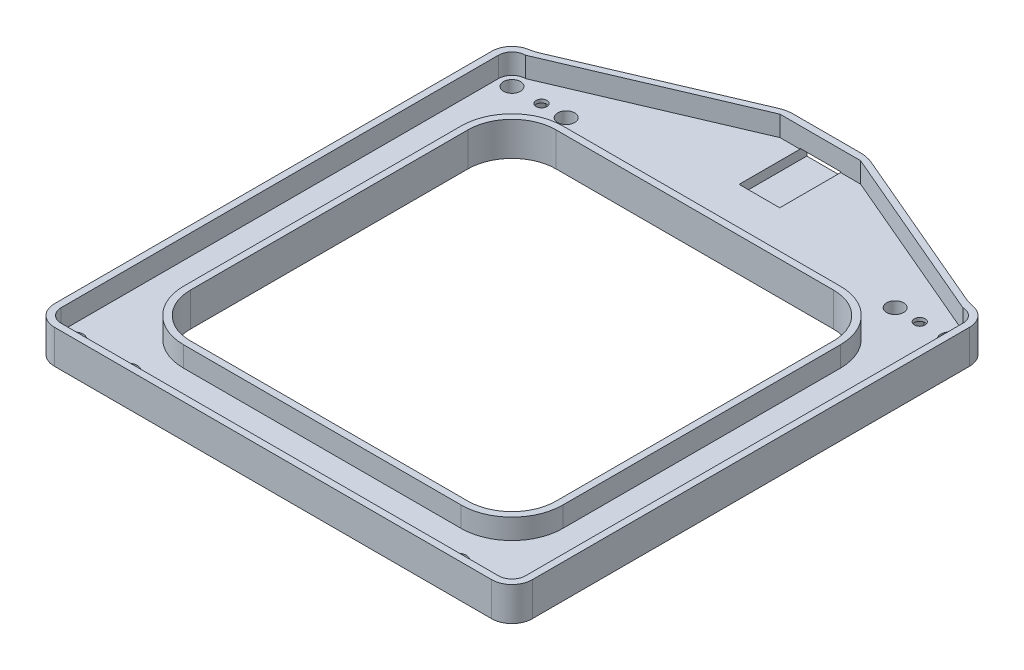
SolidWorks part; units mm, degrees
ref_plane "Front Plane" through (0, 0, 0) normal (0, 0, 1) x (1, 0, 0)
ref_plane "Top Plane" through (0, 0, 0) normal (0, 1, 0) x (1, 0, 0)
ref_plane "Right Plane" through (0, 0, 0) normal (1, 0, 0) x (0, 0, -1)
sketch "Sketch1" plane through (0, 0, 0) normal (0, 1, 0) x (1, 0, 0)
  line L0 (-64.6, 70.6) -> (-13.7811, 92.2969)
  line L5 (-64.6, -70.6) -> (64.6, -70.6)
  line L6 (-70.6, -64.6) -> (-70.6, 64.6)
  line L7 (-64.6, 70.6) -> (64.6, 70.6) construction
  line L8 (70.6, -64.6) -> (70.6, 64.6)
  line L9 (-70.6, -70.6) -> (70.6, 70.6) construction
  line L10 (-70.6, 70.6) -> (70.6, -70.6) construction
  line L11 (-41, -54) -> (41, -54)
  line L12 (-54, -41) -> (-54, 41)
  line L13 (-41, 54) -> (41, 54)
  line L14 (54, -41) -> (54, 41)
  line L15 (-54, -54) -> (54, 54) construction
  line L16 (-54, 54) -> (54, -54) construction
  line L17 (-9.8546, 93.1) -> (9.8546, 93.1)
  line L18 (13.7811, 92.2969) -> (64.6, 70.6)
  arc A0 (-70.6, -64.6) -> (-64.6, -70.6) centre (-64.6, -64.6) ccw
  arc A1 (64.6, -70.6) -> (70.6, -64.6) centre (64.6, -64.6) ccw
  arc A2 (70.6, 64.6) -> (64.6, 70.6) centre (64.6, 64.6) ccw
  arc A3 (-64.6, 70.6) -> (-70.6, 64.6) centre (-64.6, 64.6) ccw
  arc A4 (-54, -41) -> (-41, -54) centre (-41, -41) ccw
  arc A5 (41, -54) -> (54, -41) centre (41, -41) ccw
  arc A6 (54, 41) -> (41, 54) centre (41, 41) ccw
  arc A7 (-41, 54) -> (-54, 41) centre (-41, 41) ccw
  arc A8 (13.7811, 92.2969) -> (9.8546, 93.1) centre (9.8546, 83.1) ccw
  arc A9 (-9.8546, 93.1) -> (-13.7811, 92.2969) centre (-9.8546, 83.1) ccw
  point P0 (0, 0)
  point P18 (0, 0)
  point P39 (11.9, 93.1)
  point P42 (-11.9, 93.1)
  dimension "D3" = 6
  dimension "D6" = 13
  dimension "D9" = 10
  dimension "D1" = 141.2
  dimension "D2" = 141.2
  dimension "D4" = 108
  dimension "D5" = 108
  dimension "D7" = 22.5
  dimension "D8" = 23.8
extrude "Boss-Extrude1" add sketch "Sketch1" along normal blind 10
sketch "Sketch2" plane through (0, 10, 0) normal (0, 1, 0) x (1, 0, 0)
  line L0 (-64.6, 68.6) -> (-11.9, 91.1)
  line L1 (-64.6, -68.6) -> (64.6, -68.6)
  line L2 (-68.6, -64.6) -> (-68.6, 64.6)
  line L3 (-64.6, 68.6) -> (64.6, 68.6) construction
  line L4 (68.6, -64.6) -> (68.6, 64.6)
  line L5 (-68.6, -68.6) -> (68.6, 68.6) construction
  line L6 (-68.6, 68.6) -> (68.6, -68.6) construction
  line L7 (-41, -56) -> (41, -56)
  line L8 (-56, -41) -> (-56, 41)
  line L9 (-41, 56) -> (41, 56)
  line L10 (56, -41) -> (56, 41)
  line L11 (-56, -56) -> (56, 56) construction
  line L12 (-56, 56) -> (56, -56) construction
  line L13 (-11.9, 91.1) -> (11.9, 91.1)
  line L14 (11.9, 91.1) -> (64.6, 68.6)
  line L16 (-13.7811, 92.2969) -> (-64.6, 70.6) construction
  arc A0 (-68.6, -64.6) -> (-64.6, -68.6) centre (-64.6, -64.6) ccw
  arc A1 (64.6, -68.6) -> (68.6, -64.6) centre (64.6, -64.6) ccw
  arc A2 (68.6, 64.6) -> (64.6, 68.6) centre (64.6, 64.6) ccw
  arc A3 (-64.6, 68.6) -> (-68.6, 64.6) centre (-64.6, 64.6) ccw
  arc A4 (-56, -41) -> (-41, -56) centre (-41, -41) ccw
  arc A5 (41, -56) -> (56, -41) centre (41, -41) ccw
  arc A6 (56, 41) -> (41, 56) centre (41, 41) ccw
  arc A7 (-41, 56) -> (-56, 41) centre (-41, 41) ccw
  point P0 (0, 0)
  point P8 (0, 91.1)
  point P20 (0, 0)
  point P44 (0, 68.6)
  dimension "D3" = 4
  dimension "D6" = 15
  dimension "D1" = 2
  dimension "D2" = 2
  dimension "D4" = 2
  dimension "D5" = 2
  dimension "D7" = 2
extrude "Cut-Extrude1" cut sketch "Sketch2" against normal blind 6
sketch "Sketch3" plane through (0, 0, 0) normal (0, 1, 0) x (1, 0, 0)
  line L4 (0, -5.5) -> (0, 5.5) construction
  line L6 (-5.5, 0) -> (5.5, 0) construction
  circle A0 centre (-64.6, 64.6) radius 2.5
  circle A1 centre (-48.6, 64.6) radius 2.5
  circle A14 centre (-55.87, 64.6) radius 1.6
  circle A15 centre (55.87, 64.6) radius 1.6
  circle A16 centre (48.6, 64.6) radius 2.5
  circle A17 centre (64.6, 64.6) radius 2.5
  circle A18 centre (64.6, -64.6) radius 2.5
  circle A19 centre (48.6, -64.6) radius 2.5
  circle A20 centre (55.87, -64.6) radius 1.6
  circle A21 centre (-55.87, -64.6) radius 1.6
  circle A22 centre (-48.6, -64.6) radius 2.5
  circle A23 centre (-64.6, -64.6) radius 2.5
  dimension "D1" = 5
  dimension "D6" = 3.2
  dimension "D2" = 6
  dimension "D3" = 6
  dimension "D4" = 16
  dimension "D5" = 7.27
extrude "Cut-Extrude5" cut sketch "Sketch3" along normal through all
sketch "Sketch6" plane through (0, 0, 0) normal (0, -1, 0) x (1, 0, 0)
  line L0 (5.5, 0) -> (-5.5, 0) construction
  line L1 (-52.4059, 64.6) -> (-54.1379, 67.6)
  line L2 (-54.1379, 67.6) -> (-57.6021, 67.6)
  line L3 (-57.6021, 67.6) -> (-59.3341, 64.6)
  line L4 (-59.3341, 64.6) -> (-57.6021, 61.6)
  line L5 (-57.6021, 61.6) -> (-54.1379, 61.6)
  line L6 (-54.1379, 61.6) -> (-52.4059, 64.6)
  line L7 (-54.1379, -61.6) -> (-52.4059, -64.6)
  line L8 (-57.6021, -61.6) -> (-54.1379, -61.6)
  line L9 (-59.3341, -64.6) -> (-57.6021, -61.6)
  line L10 (-57.6021, -67.6) -> (-59.3341, -64.6)
  line L11 (-54.1379, -67.6) -> (-57.6021, -67.6)
  line L12 (-52.4059, -64.6) -> (-54.1379, -67.6)
  line L13 (0, -5.5) -> (0, 5.5) construction
  line L14 (52.4059, -64.6) -> (54.1379, -67.6)
  line L15 (54.1379, -67.6) -> (57.6021, -67.6)
  line L16 (57.6021, -67.6) -> (59.3341, -64.6)
  line L17 (59.3341, -64.6) -> (57.6021, -61.6)
  line L18 (57.6021, -61.6) -> (54.1379, -61.6)
  line L19 (54.1379, -61.6) -> (52.4059, -64.6)
  line L20 (54.1379, 61.6) -> (52.4059, 64.6)
  line L21 (57.6021, 61.6) -> (54.1379, 61.6)
  line L22 (59.3341, 64.6) -> (57.6021, 61.6)
  line L23 (57.6021, 67.6) -> (59.3341, 64.6)
  line L24 (54.1379, 67.6) -> (57.6021, 67.6)
  line L25 (52.4059, 64.6) -> (54.1379, 67.6)
  circle A0 centre (-55.87, 64.6) radius 3 construction
  circle A1 centre (-55.87, -64.6) radius 3 construction
  circle A2 centre (55.87, -64.6) radius 3 construction
  circle A3 centre (55.87, 64.6) radius 3 construction
  point P11 (-48.6, 64.6)
  point P22 (-48.6, -64.6)
  point P41 (48.6, -64.6)
  point P42 (48.6, 64.6)
  dimension "D1" = 6
extrude "Cut-Extrude6" cut sketch "Sketch6" against normal blind 3
fillet "Fillet1" radius 10 2 edges at (64.6, 5, -70.6) (-64.6, 5, -70.6)
sketch "Sketch7" plane through (0, 0, -93.1) normal (0, 0, -1) x (-1, 0, 0)
  line L1 (-6, 1.23) -> (6, 1.23)
  line L2 (-6, 1.23) -> (-6, 4.23)
  line L3 (-6, 4.23) -> (6, 4.23)
  line L4 (6, 1.23) -> (6, 4.23)
  line L5 (-6, 1.23) -> (6, 4.23) construction
  line L6 (-6, 4.23) -> (6, 1.23) construction
  line L7 (-6.7145, 4) -> (8.7573, 4) construction
  line L8 (-41, 4) -> (41, 4) construction
  point P0 (0, 2.73)
  dimension "D1" = 12
  dimension "D2" = 3
  dimension "D3" = 1.27
extrude "Cut-Extrude7" cut sketch "Sketch7" against normal blind 20
